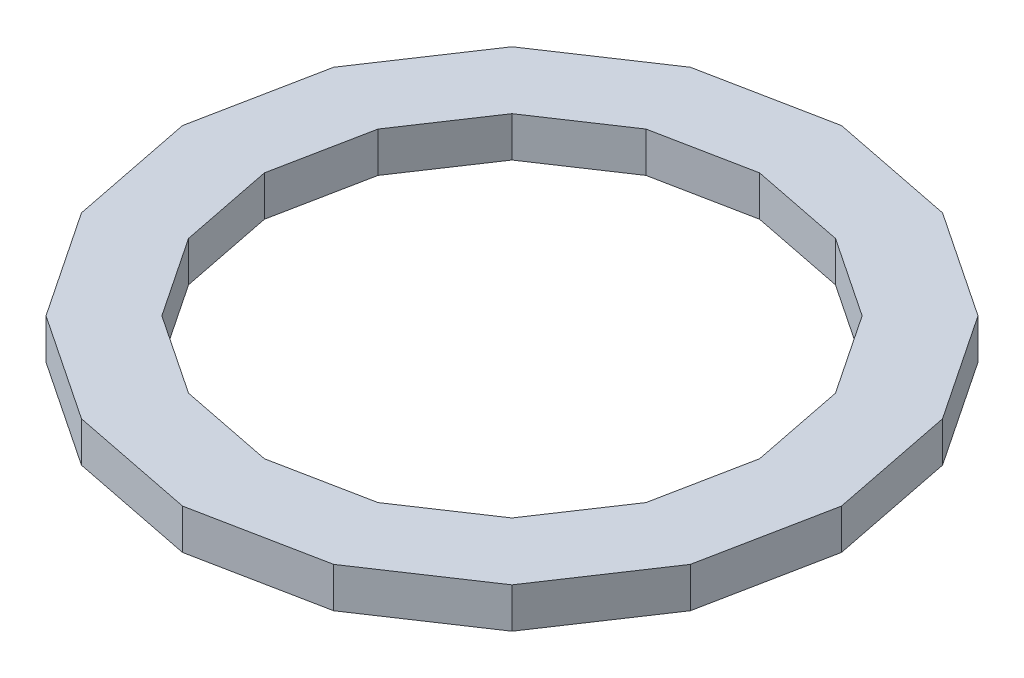
SolidWorks part; units mm, degrees
ref_plane "Front Plane" through (0, 0, 0) normal (0, 0, 1) x (1, 0, 0)
ref_plane "Top Plane" through (0, 0, 0) normal (0, 1, 0) x (1, 0, 0)
ref_plane "Right Plane" through (0, 0, 0) normal (1, 0, 0) x (0, 0, -1)
sketch "Sketch1" plane through (0, 0, 0) normal (0, 1, 0) x (1, 0, 0)
  line L1 (117.3889, 0) -> (108.4532, 44.9228)
  line L2 (108.4532, 44.9228) -> (83.0065, 83.0065)
  line L3 (83.0065, 83.0065) -> (44.9228, 108.4532)
  line L4 (44.9228, 108.4532) -> (0, 117.3889)
  line L5 (0, 117.3889) -> (-44.9228, 108.4532)
  line L6 (-44.9228, 108.4532) -> (-83.0065, 83.0065)
  line L7 (-83.0065, 83.0065) -> (-108.4532, 44.9228)
  line L8 (-108.4532, 44.9228) -> (-117.3889, 0)
  line L9 (-117.3889, 0) -> (-108.4532, -44.9228)
  line L10 (-108.4532, -44.9228) -> (-83.0065, -83.0065)
  line L11 (-83.0065, -83.0065) -> (-44.9228, -108.4532)
  line L12 (-44.9228, -108.4532) -> (0, -117.3889)
  line L13 (0, -117.3889) -> (44.9228, -108.4532)
  line L14 (44.9228, -108.4532) -> (83.0065, -83.0065)
  line L15 (83.0065, -83.0065) -> (108.4532, -44.9228)
  line L16 (108.4532, -44.9228) -> (117.3889, 0)
  line L17 (156.2353, 0) -> (144.3426, 59.7887)
  line L18 (144.3426, 59.7887) -> (110.4751, 110.4751)
  line L19 (110.4751, 110.4751) -> (59.7887, 144.3426)
  line L20 (59.7887, 144.3426) -> (0, 156.2353)
  line L21 (0, 156.2353) -> (-59.7887, 144.3426)
  line L22 (-59.7887, 144.3426) -> (-110.4751, 110.4751)
  line L23 (-110.4751, 110.4751) -> (-144.3426, 59.7887)
  line L24 (-144.3426, 59.7887) -> (-156.2353, 0)
  line L25 (-156.2353, 0) -> (-144.3426, -59.7887)
  line L26 (-144.3426, -59.7887) -> (-110.4751, -110.4751)
  line L27 (-110.4751, -110.4751) -> (-59.7887, -144.3426)
  line L28 (-59.7887, -144.3426) -> (0, -156.2353)
  line L29 (0, -156.2353) -> (59.7887, -144.3426)
  line L30 (59.7887, -144.3426) -> (110.4751, -110.4751)
  line L31 (110.4751, -110.4751) -> (144.3426, -59.7887)
  line L32 (144.3426, -59.7887) -> (156.2353, 0)
  circle A0 centre (0, 0) radius 115.1333 construction
  circle A1 centre (0, 0) radius 153.2333 construction
  dimension "D1" = 60.96
  dimension "D2" = 38.1
extrude "Boss-Extrude1" add sketch "Sketch1" along normal blind 19.05
